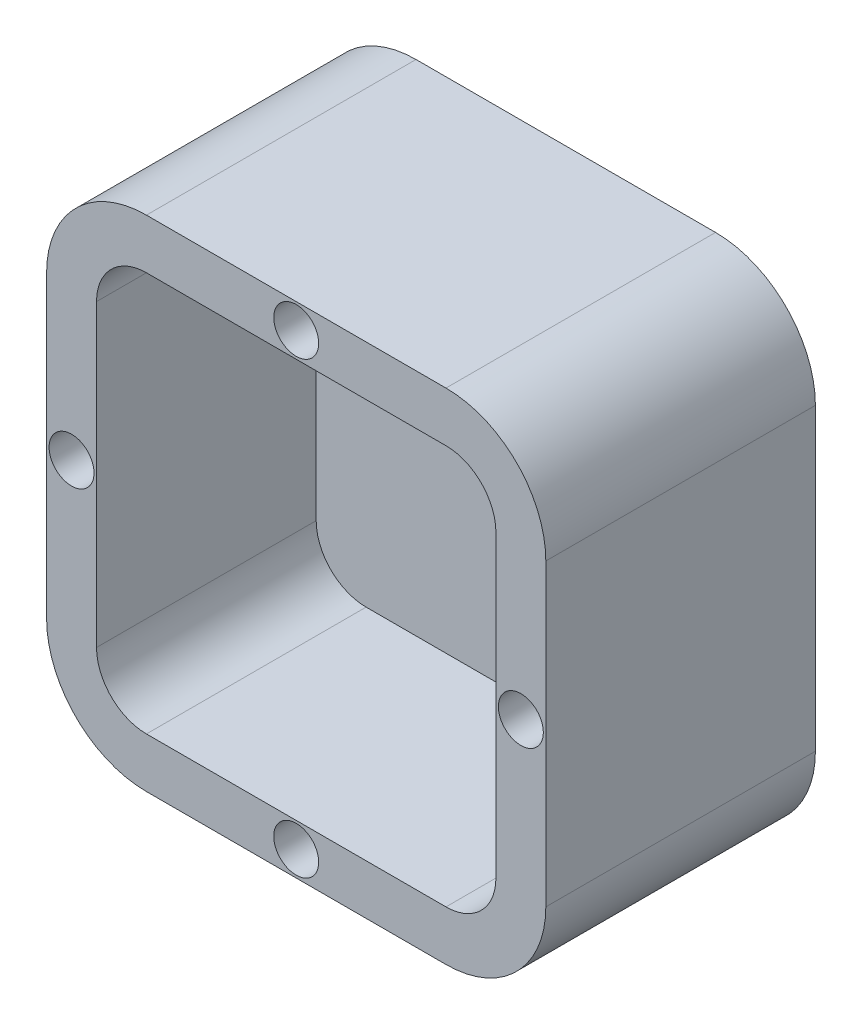
SolidWorks part; units mm, degrees
material "Custom Plastic"
ref_plane "Front Plane" through (0, 0, 0) normal (0, 0, 1) x (1, 0, 0)
ref_plane "Top Plane" through (0, 0, 0) normal (0, 1, 0) x (1, 0, 0)
ref_plane "Right Plane" through (0, 0, 0) normal (1, 0, 0) x (0, 0, -1)
sketch "Sketch1" plane through (0, 0, 0) normal (0, 0, 1) x (1, 0, 0)
  line L1 (0, 0) -> (50, 0)
  line L2 (0, 0) -> (0, 50)
  line L3 (0, 50) -> (50, 50)
  line L4 (50, 0) -> (50, 50)
  dimension "D1" = 50
  dimension "D2" = 50
extrude "Boss-Extrude1" add sketch "Sketch1" along normal blind 27
fillet "Fillet1" radius 10 4 edges at (0, 0, 13.5) (50, 0, 13.5) (50, 50, 13.5) (0, 50, 13.5)
shell "Shell1" thickness 5
sketch "Sketch3" plane through (0, 0, 5) normal (0, 0, 1) x (1, 0, 0)
  line L0 (5, 25) -> (45, 25) construction
  line L4 (10, 5) -> (40, 5)
  line L5 (45, 10) -> (45, 40)
  line L6 (40, 45) -> (10, 45)
  line L7 (5, 40) -> (5, 10)
  line L8 (10, 5) -> (40, 5) construction
  line L9 (45, 10) -> (45, 40) construction
  line L10 (40, 45) -> (10, 45) construction
  line L11 (5, 40) -> (5, 10) construction
  circle A0 centre (25, 25) radius 7 construction
  circle A1 centre (25, 32) radius 1.55
  circle A2 centre (25, 18) radius 1.55
  arc A4 (40, 5) -> (45, 10) centre (40, 10) ccw
  arc A5 (45, 40) -> (40, 45) centre (40, 40) ccw
  arc A6 (10, 45) -> (5, 40) centre (10, 40) ccw
  arc A7 (5, 10) -> (10, 5) centre (10, 10) ccw
  arc A8 (40, 5) -> (45, 10) centre (40, 10) ccw construction
  arc A9 (45, 40) -> (40, 45) centre (40, 40) ccw construction
  arc A10 (10, 45) -> (5, 40) centre (10, 40) ccw construction
  arc A11 (5, 10) -> (10, 5) centre (10, 10) ccw construction
  dimension "D2" = 14
  dimension "D3" = 3.1
  dimension "D4" = 3.1
  dimension "D1" = 0
extrude "Cut-Extrude1" cut sketch "Sketch3" against normal up to surface (5 mm away) contours A1 | A2 up to face at (25, 25, 0)
sketch "Sketch4" plane through (0, 0, 27) normal (0, 0, 1) x (1, 0, 0)
  line L0 (47.0711, 2.9289) -> (2.9289, 47.0711) construction
  arc A0 (40, 0) -> (50, 10) centre (40, 10) ccw construction
  arc A1 (10, 50) -> (0, 40) centre (10, 40) ccw construction
  circle A2 centre (25, 25) radius 22.5 construction
  circle A3 centre (25, 2.5) radius 2.25
  circle A4 centre (2.5, 25) radius 2.25
  circle A5 centre (25, 47.5) radius 2.25
  circle A6 centre (47.5, 25) radius 2.25
  dimension "D1" = 45
  dimension "D2" = 4.5
  dimension "D3" = 4
extrude "Cut-Extrude2" cut sketch "Sketch4" against normal blind 5
